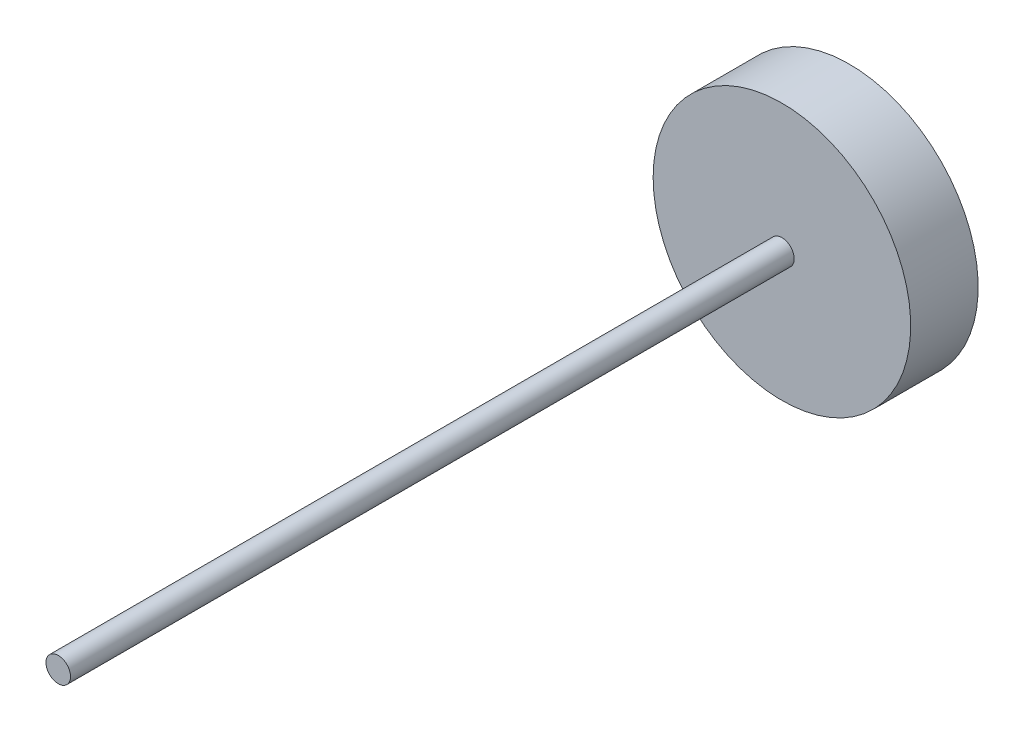
SolidWorks part; units mm, degrees
ref_plane "Front Plane" through (0, 0, 0) normal (0, 0, 1) x (1, 0, 0)
ref_plane "Top Plane" through (0, 0, 0) normal (0, 1, 0) x (1, 0, 0)
ref_plane "Right Plane" through (0, 0, 0) normal (1, 0, 0) x (0, 0, -1)
sketch "Sketch1" plane through (0, 0, 0) normal (0, 0, 1) x (1, 0, 0)
  circle A0 centre (0, 0) radius 88
extrude "Boss-Extrude3" add sketch "Sketch1" along normal blind 25
sketch "Sketch4" plane through (0, 0, 25) normal (0, 0, 1) x (1, 0, 0)
  line L0 (0, 88) -> (0, 100) construction
  line L1 (5.236, 100) -> (-5.236, 100)
  line L2 (-5.236, 100) -> (-5.236, 86.6488)
  line L3 (-5.236, 86.6488) -> (5.236, 86.6488)
  line L4 (5.236, 86.6488) -> (5.236, 100)
  circle A0 centre (0, 0) radius 88 construction
  point P9 (0, 100)
extrude "Boss-Extrude4" add sketch "Sketch4" against normal blind 25
fillet "Fillet2" radius 4 4 edges at (-5.236, 100, 12.5) (0, 100, 0) (5.236, 100, 12.5) (0, 100, 25)
pattern_circular "CirPattern1" count 30 over 360 about axis through (0, 0.3177, 0) along (0, 0, 1) of "Fillet2", "Boss-Extrude4"
ref_plane "Plane1" through (-5.236, 96, 25) normal (-1, 0, 0) x (0, 0, 1)
sketch "Sketch6" plane through (0, 0, 25) normal (0, 0, 1) x (1, 0, 0)
  circle A0 centre (0, 0) radius 10
extrude "Boss-Extrude5" add sketch "Sketch6" along normal blind 60
sketch "Sketch7" plane through (0, 0, 0) normal (0, 0, -1) x (-1, 0, 0)
  circle A0 centre (0, 0) radius 10
extrude "Boss-Extrude6" add sketch "Sketch7" along normal blind 10
sketch "Sketch8" plane through (0, 0, 85) normal (0, 0, 1) x (1, 0, 0)
  circle A0 centre (0, 0) radius 10
extrude "Boss-Extrude7" add sketch "Sketch8" along normal blind 10
sketch "Sketch9" plane through (0, 0, 95) normal (0, 0, 1) x (1, 0, 0)
  circle A0 centre (0, 0) radius 10
extrude "Boss-Extrude8" add sketch "Sketch9" along normal blind 25
sketch "Sketch10" plane through (0, 0, 120) normal (0, 0, 1) x (1, 0, 0)
  circle A0 centre (0, 0) radius 10
extrude "Boss-Extrude9" add sketch "Sketch10" along normal blind 42.5
sketch "Sketch12" plane through (0, 0, 162.5) normal (0, 0, 1) x (1, 0, 0)
  circle A0 centre (0, 0) radius 12.5
extrude "Cut-Extrude1" cut sketch "Sketch12" against normal blind 12
sketch "Sketch13" plane through (0, 0, 150.5) normal (0, 0, 1) x (1, 0, 0)
  circle A0 centre (0, 0) radius 10
extrude "Cut-Extrude2" cut sketch "Sketch13" against normal blind 55.5
sketch "Sketch14" plane through (0, 0, 95) normal (0, 0, 1) x (1, 0, 0)
  circle A0 centre (0, 0) radius 10
extrude "Boss-Extrude10" add sketch "Sketch14" along normal blind 440
sketch "Sketch15" plane through (0, 0, 0) normal (0, 0, -1) x (-1, 0, 0)
  circle A0 centre (0, 0) radius 105
extrude "Boss-Extrude12" add sketch "Sketch15" against normal blind 25
sketch "Sketch16" plane through (0, 0, 0) normal (0, 0, -1) x (-1, 0, 0)
  circle A0 centre (0, 0) radius 105
extrude "Boss-Extrude13" add sketch "Sketch16" along normal blind 30
sketch "Sketch17" plane through (0, 0, 535) normal (0, 0, 1) x (1, 0, 0)
  circle A0 centre (0, 0) radius 10
extrude "Boss-Extrude14" add sketch "Sketch17" along normal blind 50
sketch "Sketch18" plane through (0, 0, 585) normal (0, 0, 1) x (1, 0, 0)
  circle A0 centre (0, 0) radius 10
extrude "Boss-Extrude15" add sketch "Sketch18" along normal blind 30
